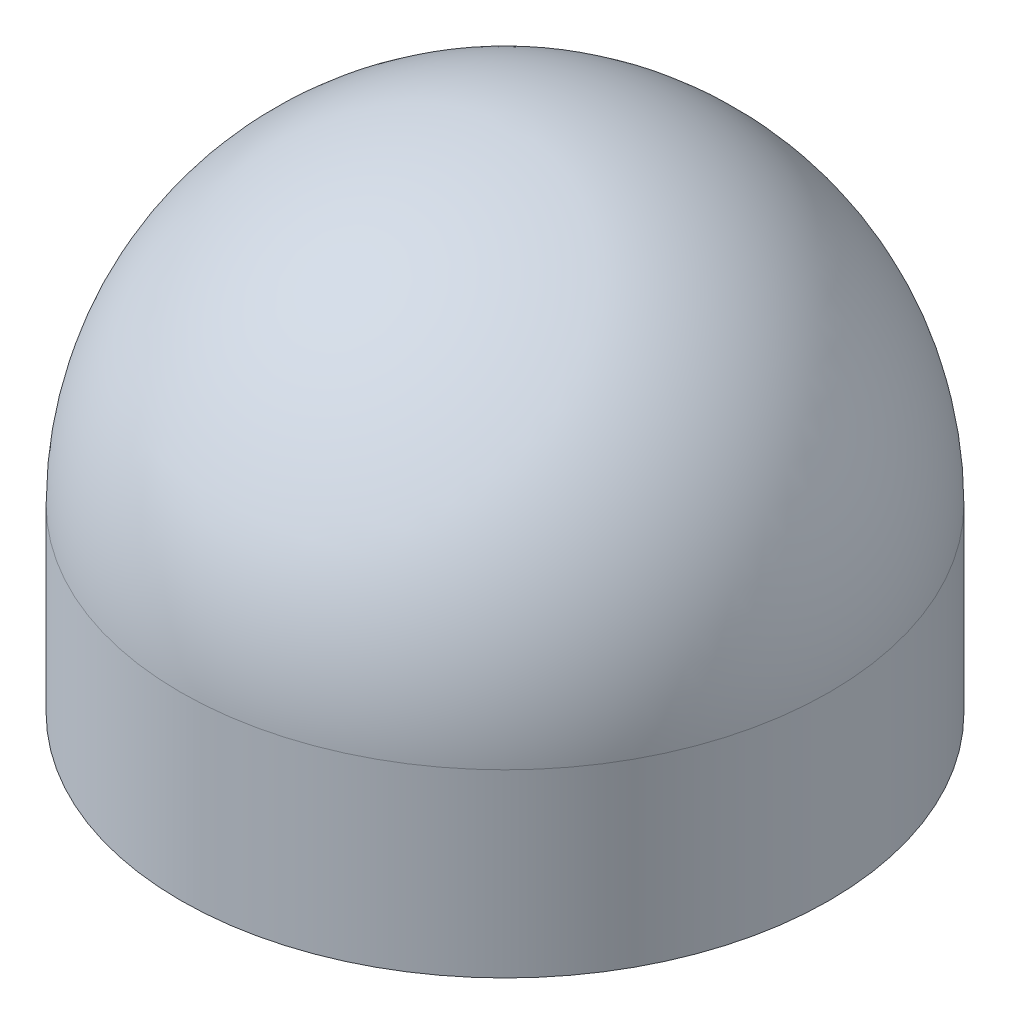
SolidWorks part; units mm, degrees
ref_plane "前视基准面" through (0, 0, 0) normal (0, 0, 1) x (1, 0, 0)
ref_plane "上视基准面" through (0, 0, 0) normal (0, 1, 0) x (1, 0, 0)
ref_plane "右视基准面" through (0, 0, 0) normal (1, 0, 0) x (0, 0, -1)
other "Configuration Table"
sketch "草图1" plane through (0, 0, 0) normal (0, 1, 0) x (1, 0, 0)
  line L0 (0, 9) -> (0, -9)
  arc A0 (0, -9) -> (0, 9) centre (0, 0) ccw
  dimension "D1" = 18
revolve "旋转1" add sketch "草图1" angle 180 about L0
sketch "草图6" plane through (0, 0, 0) normal (1, 0, 0) x (0, 0, -1)
  line L1 (0, 0) -> (9, 0)
  line L2 (0, 0) -> (0, -5)
  line L3 (0, -5) -> (9, -5)
  line L4 (9, 0) -> (9, -5)
  dimension "D1" = 9
  dimension "D2" = 5
revolve "旋转2" add sketch "草图6" angle 360 about L2
sketch "草图7" plane through (0, 0, 0) normal (1, 0, 0) x (0, 0, -1)
  line L0 (-9, -5) -> (9, -5) construction
  line L1 (0, -0.1037) -> (8, -0.1037)
  line L2 (0, -0.1037) -> (0, -5)
  line L3 (0, -5) -> (8, -5)
  line L4 (8, -0.1037) -> (8, -5)
  dimension "D1" = 8
revolve "切除-旋转2" cut sketch "草图7" angle 360 about L2
